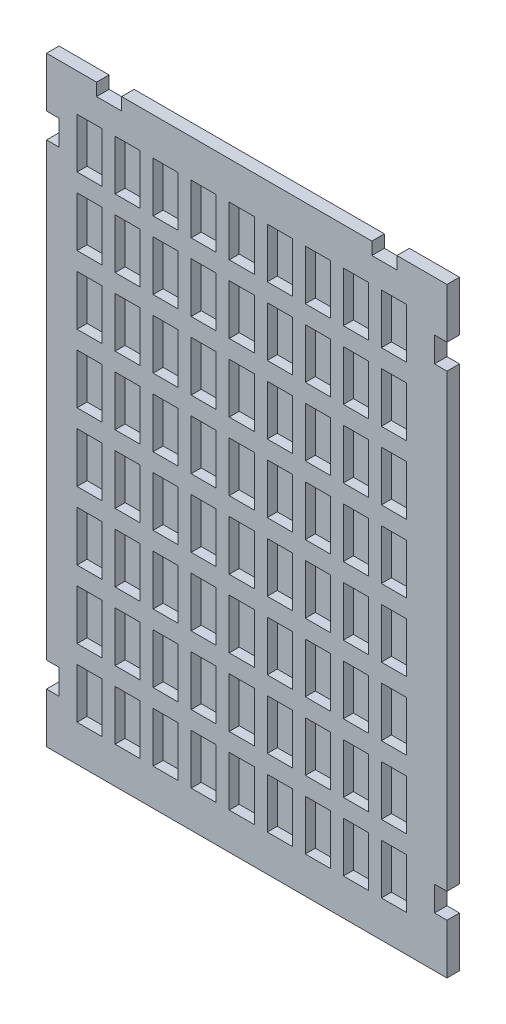
SolidWorks part; units mm, degrees
ref_plane "Front Plane" through (0, 0, 0) normal (0, 0, 1) x (1, 0, 0)
ref_plane "Top Plane" through (0, 0, 0) normal (0, 1, 0) x (1, 0, 0)
ref_plane "Right Plane" through (0, 0, 0) normal (1, 0, 0) x (0, 0, -1)
sketch "Sketch1" plane through (0, 0, 0) normal (0, 0, 1) x (1, 0, 0)
  line L0 (12.7, -152.4) -> (88.9, -152.4)
  line L1 (0, 0) -> (101.6, 0)
  line L2 (0, 0) -> (0, -152.4)
  line L3 (0, -152.4) -> (12.7, -152.4)
  line L4 (101.6, 0) -> (101.6, -152.4)
  line L5 (12.7, 0) -> (19.05, 0)
  line L6 (12.7, 0) -> (12.7, -3.175)
  line L7 (12.7, -3.175) -> (19.05, -3.175)
  line L8 (19.05, 0) -> (19.05, -3.175)
  line L9 (82.55, 0) -> (88.9, 0)
  line L10 (82.55, 0) -> (82.55, -3.175)
  line L11 (82.55, -3.175) -> (88.9, -3.175)
  line L12 (88.9, 0) -> (88.9, -3.175)
  line L13 (101.6, -12.7) -> (98.425, -12.7)
  line L14 (101.6, -12.7) -> (101.6, -19.05)
  line L15 (101.6, -19.05) -> (98.425, -19.05)
  line L16 (98.425, -12.7) -> (98.425, -19.05)
  line L17 (101.6, -133.35) -> (98.425, -133.35)
  line L18 (101.6, -133.35) -> (101.6, -139.7)
  line L19 (101.6, -139.7) -> (98.425, -139.7)
  line L20 (98.425, -133.35) -> (98.425, -139.7)
  line L25 (88.9, -152.4) -> (101.6, -152.4)
  line L29 (0, -139.7) -> (3.175, -139.7)
  line L30 (0, -139.7) -> (0, -133.35)
  line L31 (0, -133.35) -> (3.175, -133.35)
  line L32 (3.175, -139.7) -> (3.175, -133.35)
  line L33 (0, -19.05) -> (3.175, -19.05)
  line L34 (0, -19.05) -> (0, -12.7)
  line L35 (0, -12.7) -> (3.175, -12.7)
  line L36 (3.175, -19.05) -> (3.175, -12.7)
  dimension "D1" = 101.6
  dimension "D2" = 152.4
  dimension "D3" = 12.7
  dimension "D4" = 6.35
  dimension "D5" = 3.175
  dimension "D6" = 6.35
  dimension "D7" = 3.175
  dimension "D8" = 12.7
  dimension "D9" = 12.7
  dimension "D10" = 6.35
  dimension "D11" = 3.175
  dimension "D12" = 3.175
  dimension "D13" = 6.35
  dimension "D14" = 12.7
  dimension "D21" = 3.175
  dimension "D22" = 6.35
  dimension "D23" = 12.7
  dimension "D24" = 12.7
  dimension "D25" = 6.35
  dimension "D26" = 3.175
extrude "Boss-Extrude1" add sketch "Sketch1" along normal blind 3.175
sketch "Sketch2" plane through (0, 0, 3.175) normal (0, 0, 1) x (1, 0, 0)
  line L0 (12.7, -3.175) -> (19.05, -3.175) construction
  line L1 (7.747, -9.525) -> (14.097, -9.525)
  line L2 (7.747, -9.525) -> (7.747, -22.225)
  line L3 (7.747, -22.225) -> (14.097, -22.225)
  line L4 (14.097, -9.525) -> (14.097, -22.225)
  line L5 (7.747, -9.525) -> (14.097, -22.225) construction
  line L6 (7.747, -22.225) -> (14.097, -9.525) construction
  line L7 (3.175, -19.05) -> (3.175, -12.7) construction
  point P0 (10.922, -15.875)
  dimension "D1" = 6.35
  dimension "D2" = 4.572
  dimension "D3" = 6.35
  dimension "D4" = 12.7
extrude "Cut-Extrude1" cut sketch "Sketch2" against normal blind 2.54
pattern_linear "LPattern1" count 9 spacing 9.652 along (1, 0, 0) count 8 spacing 17.272 along (0, -1, 0) of "Cut-Extrude1"
